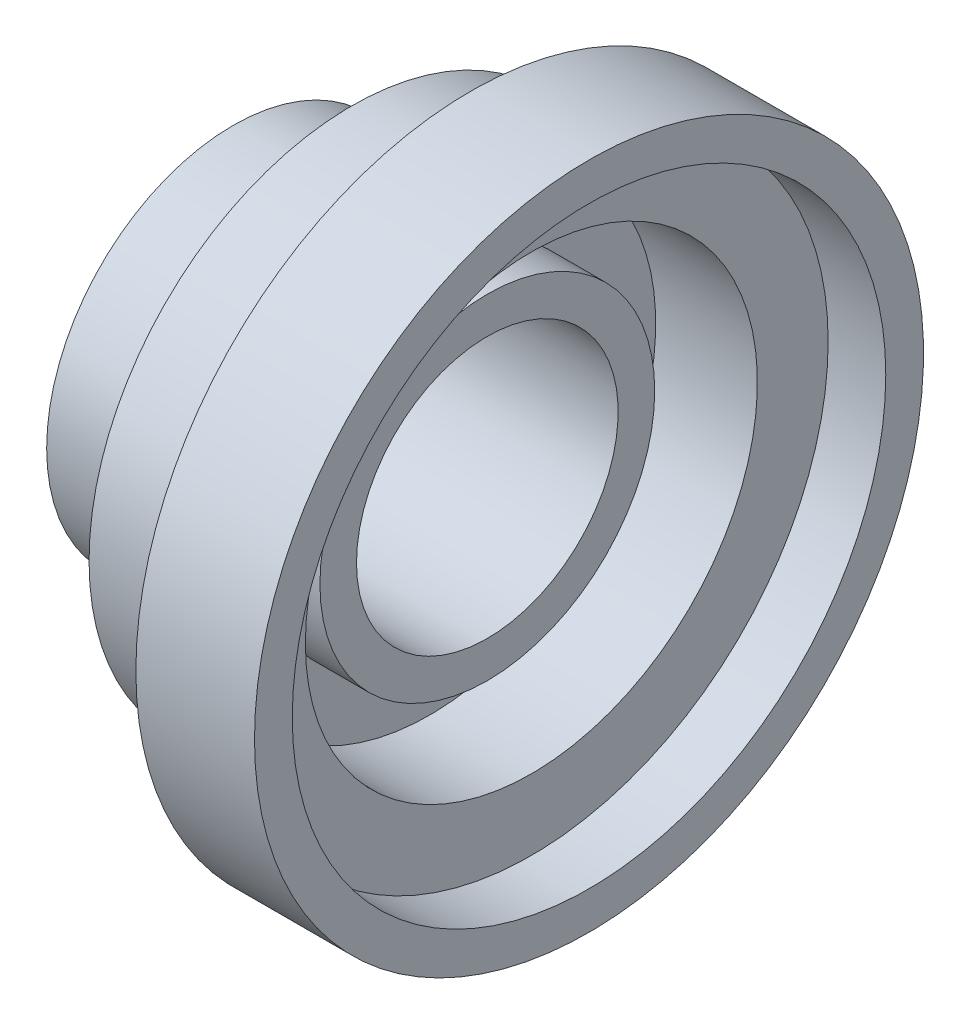
SolidWorks part; units mm, degrees
ref_plane "Front Plane" through (0, 0, 0) normal (0, 0, 1) x (1, 0, 0)
ref_plane "Top Plane" through (0, 0, 0) normal (0, 1, 0) x (1, 0, 0)
ref_plane "Right Plane" through (0, 0, 0) normal (1, 0, 0) x (0, 0, -1)
sketch "Croquis1" plane through (0, 0, 0) normal (0, 0, 1) x (1, 0, 0)
  line L0 (0, 0) -> (0, 16.401)
  line L1 (0, 16.401) -> (35, 16.401)
  line L2 (35, 16.401) -> (35, 38.901)
  line L3 (35, 38.901) -> (70, 38.901)
  line L4 (70, 38.901) -> (70, 60.0898)
  line L5 (70, 60.0898) -> (105, 60.0898)
  line L6 (105, 60.0898) -> (105, 48.9504)
  line L7 (105, 48.9504) -> (88, 48.9504)
  line L8 (88, 48.9504) -> (88, 28.0837)
  line L9 (88, 28.0837) -> (58, 28.0837)
  line L10 (58, 28.0837) -> (58, 10.7911)
  line L11 (58, 10.7911) -> (75, 10.7911)
  line L12 (75, 10.7911) -> (75, 0)
  line L13 (75, 0) -> (0, 0)
  line L14 (0, -38.599) -> (105, -38.599) construction
  dimension "D1" = 17
  dimension "D2" = 30
  dimension "D3" = 35
  dimension "D4" = 35
  dimension "D5" = 105
  dimension "D6" = 110
  dimension "D7" = 155
  dimension "D8" = 75
revolve "Revolución1" add sketch "Croquis1" angle 360 about L14
